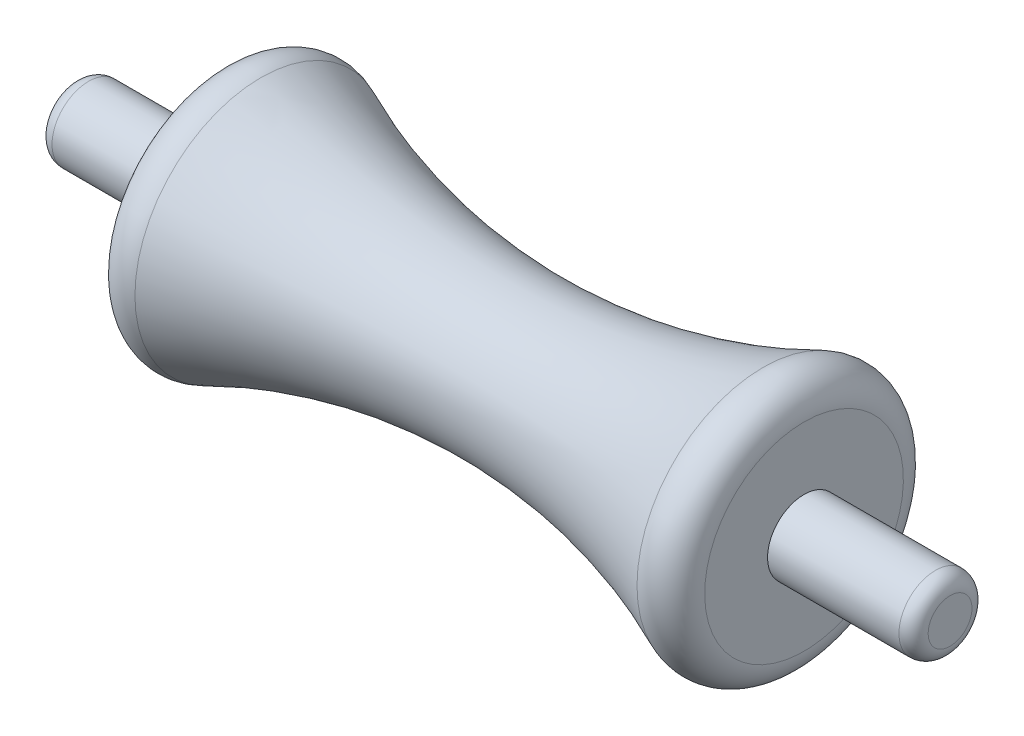
SolidWorks part; units mm, degrees
material "ABS"
ref_plane "Front Plane" through (0, 0, 0) normal (0, 0, 1) x (1, 0, 0)
ref_plane "Top Plane" through (0, 0, 0) normal (0, 1, 0) x (1, 0, 0)
ref_plane "Right Plane" through (0, 0, 0) normal (1, 0, 0) x (0, 0, -1)
sketch "Sketch1" plane through (0, 0, 0) normal (0, 0, 1) x (1, 0, 0)
  line L0 (60, 0) -> (-60, 0)
  line L1 (-60, 0) -> (-60, -3)
  line L2 (-58, -5) -> (-40, -5)
  line L3 (-40, -5) -> (-40, -13.6059)
  line L4 (0, 0) -> (0, -10) construction
  line L5 (40, -5) -> (40, -13.6059)
  line L6 (58, -5) -> (40, -5)
  line L7 (60, 0) -> (60, -3)
  arc A0 (-34.382, -17.2641) -> (34.382, -17.2641) centre (0, -95) cw
  arc A1 (58, -5) -> (60, -3) centre (58, -3) ccw
  arc A2 (-60, -3) -> (-58, -5) centre (-58, -3) ccw
  arc A3 (40, -13.6059) -> (34.382, -17.2641) centre (36, -13.6059) cw
  arc A4 (-40, -13.6059) -> (-34.382, -17.2641) centre (-36, -13.6059) ccw
  point P4 (0, 0)
  point P13 (0, 0)
  point P14 (0, 0)
  point P15 (0, 0)
  point P16 (0, 0)
  point P17 (0, -10)
  point P20 (60, -5)
  point P23 (-60, -5)
  point P26 (40, -20)
  point P29 (-40, -20)
  dimension "D6" = 2
  dimension "D7" = 4
  dimension "D1" = 120
  dimension "D2" = 5
  dimension "D3" = 20
  dimension "D4" = 15
  dimension "D5" = 10
revolve "Revolve1" add sketch "Sketch1" angle 360 about L0
